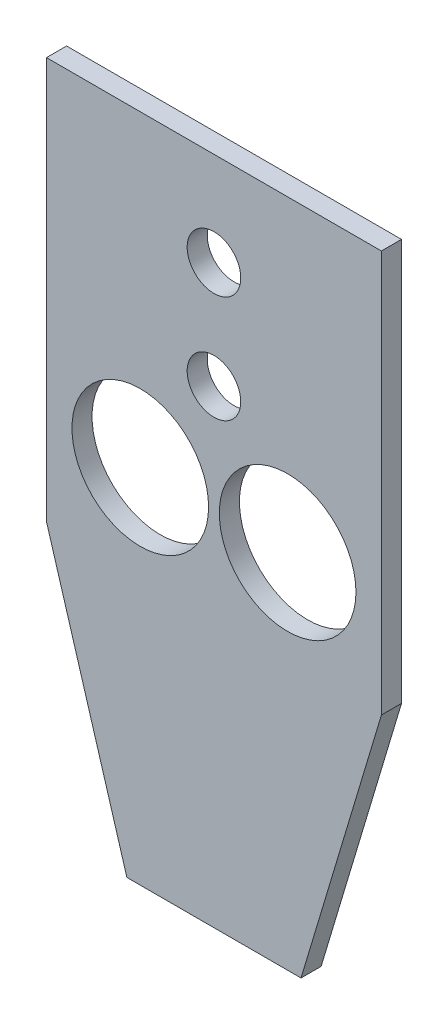
SolidWorks part; units mm, degrees
material "Mahogany"
ref_plane "Front Plane" through (0, 0, 0) normal (0, 0, 1) x (1, 0, 0)
ref_plane "Top Plane" through (0, 0, 0) normal (0, 1, 0) x (1, 0, 0)
ref_plane "Right Plane" through (0, 0, 0) normal (1, 0, 0) x (0, 0, -1)
sketch "Sketch1" plane through (0, 0, 0) normal (0, 0, 1) x (1, 0, 0)
  line L1 (0, 0) -> (-250, 0)
  line L2 (0, 0) -> (0, 300)
  line L3 (0, 300) -> (-250, 300)
  line L4 (-250, 0) -> (-250, 300)
  circle A0 centre (-125, 230) radius 20
  circle A1 centre (-125, 150) radius 20
  circle A2 centre (-180, 70) radius 51
  circle A3 centre (-70, 70) radius 51
  dimension "D3" = 40
  dimension "D4" = 40
  dimension "D9" = 102
  dimension "D12" = 102
  dimension "D14" = 70
  dimension "D1" = 250
  dimension "D2" = 300
  dimension "D5" = 125
  dimension "D6" = 70
  dimension "D7" = 125
  dimension "D8" = 80
  dimension "D10" = 70
  dimension "D11" = 70
  dimension "D13" = 70
extrude "Boss-Extrude1" add sketch "Sketch1" along normal blind 15
sketch "Sketch2" plane through (0, 0, 0) normal (0, 0, 1) x (1, 0, 0)
  line L0 (-250, 0) -> (0, 0) construction
  line L1 (-190, 0) -> (-60, 0)
  line L3 (-190, -200) -> (-60, -200)
  line L7 (-250, 0) -> (-190, -200)
  line L8 (-60, -200) -> (0, 0)
  line L9 (-190, 0) -> (-250, 0)
  line L10 (-60, 0) -> (0, 0)
  dimension "D3" = 200
extrude "Boss-Extrude2" add sketch "Sketch2" along normal blind 15
